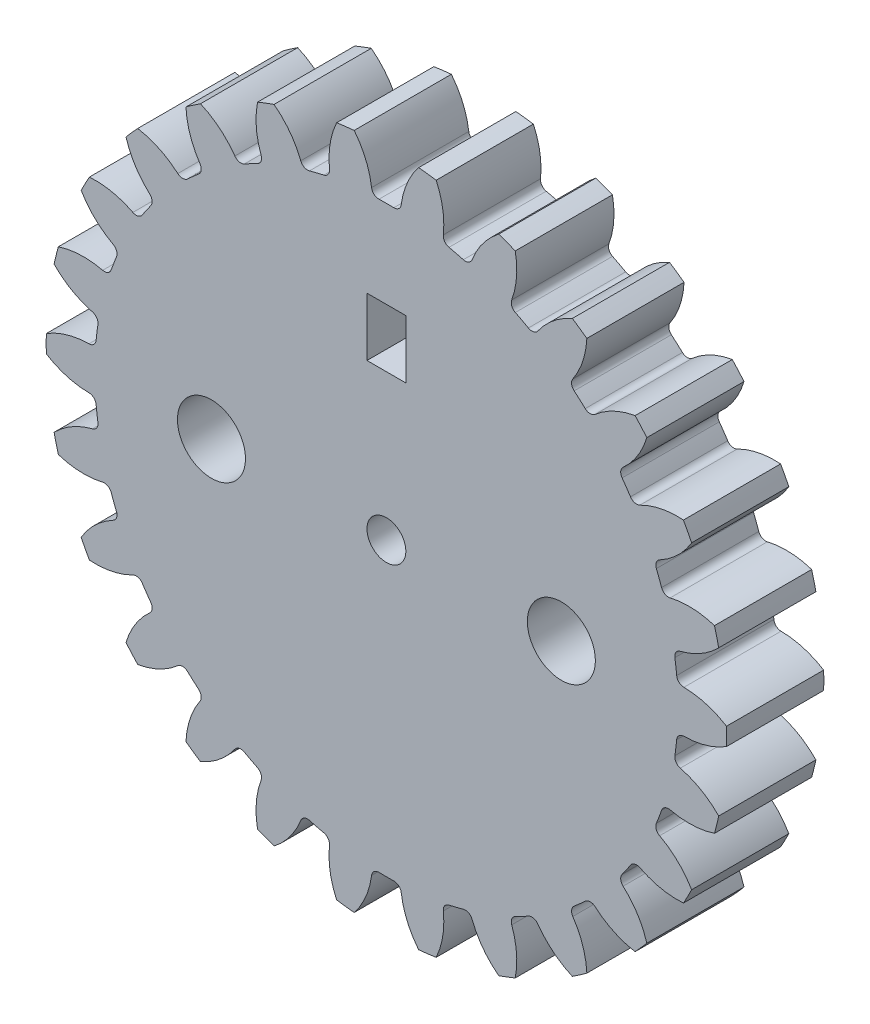
SolidWorks part; units mm, degrees
ref_plane "Front" through (0, 0, 0) normal (0, 0, 1) x (1, 0, 0)
ref_plane "Top" through (0, 0, 0) normal (0, 1, 0) x (1, 0, 0)
ref_plane "Right" through (0, 0, 0) normal (1, 0, 0) x (0, 0, -1)
sketch "Sketch1" plane through (0, 0, 0) normal (0, 0, 1) x (1, 0, 0)
  circle A0 centre (0, 0) radius 15
  circle A1 centre (0, 0) radius 17.5
  circle A2 centre (0, 0) radius 16.25
  dimension "D1" = 35
  dimension "D2" = 30
  dimension "D3" = 32.5
extrude "Boss-Extrude1" add sketch "Sketch1" along normal mid plane 5 contours A1
sketch "Sketch3" plane through (0, 0, 0) normal (0, 0, 1) x (1, 0, 0)
  line L0 (0, 0) -> (0, 17.5) construction
  line L1 (0, 0) -> (-0.7315, 14.9822) construction
  line L2 (-0.9812, 16.2204) -> (0.9812, 16.2204) construction
  line L3 (-1.4257, 17.4418) -> (0, 13.5247) construction
  line L4 (0, 0) -> (2.1094, 17.3724) construction
  line L5 (0.9812, 16.2204) -> (2.9291, 15.9838) construction
  arc A0 (-0.7315, 14.9822) -> (0.7315, 14.9822) centre (0, 0) cw
  arc A4 (1.6577, 17.4213) -> (-1.6577, 17.4213) centre (0, 0) ccw
  circle A5 centre (0, 0) radius 17.5 construction
  arc A7 (-1.6577, 17.4213) -> (-0.7315, 14.9822) centre (-4.9488, 14.7762) cw
  arc A10 (1.6577, 17.4213) -> (0.7315, 14.9822) centre (4.9488, 14.7762) ccw
  circle A11 centre (0, 0) radius 15 construction
  circle A12 centre (0, 0) radius 16.25 construction
  dimension "D1" = 20
  dimension "D2" = 6.923
extrude "Cut-Extrude1" cut sketch "Sketch3" against normal through all both and the other way through all
fillet "Fillet2" radius 0.375 2 edges at (0.7315, 14.9822, 0) (-0.7315, 14.9822, 0)
pattern_circular "CirPattern1" count 26 over 360 about axis through (0, 0, 0) along (0, 0, 1) of "Cut-Extrude1", "Fillet2"
sketch "Sketch4" plane through (0, 0, 0) normal (0, 0, 1) x (1, 0, 0)
  circle A0 centre (0, 0) radius 1
  dimension "D1" = 2
extrude "String_Hole" cut sketch "Sketch4" against normal through all both and the other way through all
sketch "Sketch5" plane through (0, 0, 0) normal (0, 0, 1) x (1, 0, 0)
  line L0 (-9, 0) -> (9, 0) construction
  circle A0 centre (9, 0) radius 1.75
  circle A1 centre (-9, 0) radius 1.75
  dimension "D2" = 3.5
  dimension "D1" = 18
extrude "To_Knuckle_Mount" cut sketch "Sketch5" against normal through all both and the other way through all
sketch "Sketch6" plane through (0, 0, 2.5) normal (0, 0, 1) x (1, 0, 0)
  line L0 (0, 0) -> (0, 15) construction
  line L2 (1, 7.5) -> (-1, 7.5)
  line L3 (1, 7.5) -> (1, 10.5)
  line L4 (1, 10.5) -> (-1, 10.5)
  line L5 (-1, 7.5) -> (-1, 10.5)
  line L6 (1, 7.5) -> (-1, 10.5) construction
  line L7 (1, 10.5) -> (-1, 7.5) construction
  arc A2 (0.3805, 14.9952) -> (-0.3805, 14.9952) centre (0, 0) ccw construction
  point P6 (0, 9)
  dimension "D1" = 2
  dimension "D2" = 3
  dimension "D3" = 9
extrude "For_Alignment" cut sketch "Sketch6" against normal blind 2
equation "\"od\"= 35'outside diameter"
equation "\"n\"= 26'number of teeth"
equation "\"m\"= \"od\" / ( \"n\" + 2 )'module"
equation "\"p\"= \"m\" * pi'pitch"
equation "\"d\"= \"m\" * \"n\"'primitive diameter"
equation "\"da\"= \"d\" + 2 * \"m\"'head diamater"
equation "\"df\"= \"d\" - 2 * \"m\"'foot diameter"
equation "\"D1@Sketch1\"=\"od\""
equation "\"D2@Sketch1\"=\"df\""
equation "\"D3@Sketch1\"=\"d\""
equation "\"D2@Sketch3\"=180/\"n\""
equation "\"D1@Fillet2\"=.3*\"m\""
equation "\"D1@CirPattern1\"=\"n\""
